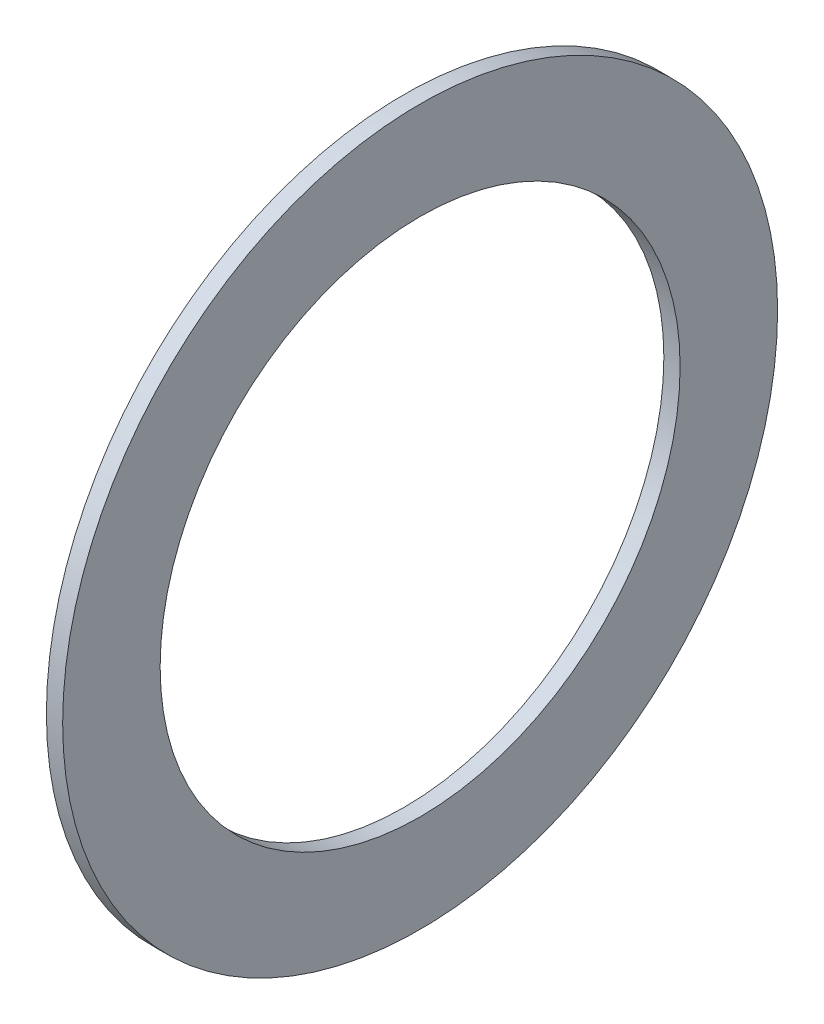
SolidWorks part; units mm, degrees
ref_plane "Front Plane" through (0, 0, 0) normal (0, 0, 1) x (1, 0, 0)
ref_plane "Top Plane" through (0, 0, 0) normal (0, 1, 0) x (1, 0, 0)
ref_plane "Right Plane" through (0, 0, 0) normal (1, 0, 0) x (0, 0, -1)
sketch "Sketch1" plane through (0, 0, 0) normal (1, 0, 0) x (0, 0, -1)
  circle A0 centre (0, 0) radius 4
  circle A1 centre (0, 0) radius 5.5
  dimension "D1" = 8
  dimension "D2" = 11
extrude "Boss-Extrude1" add sketch "Sketch1" along normal blind 0.25
